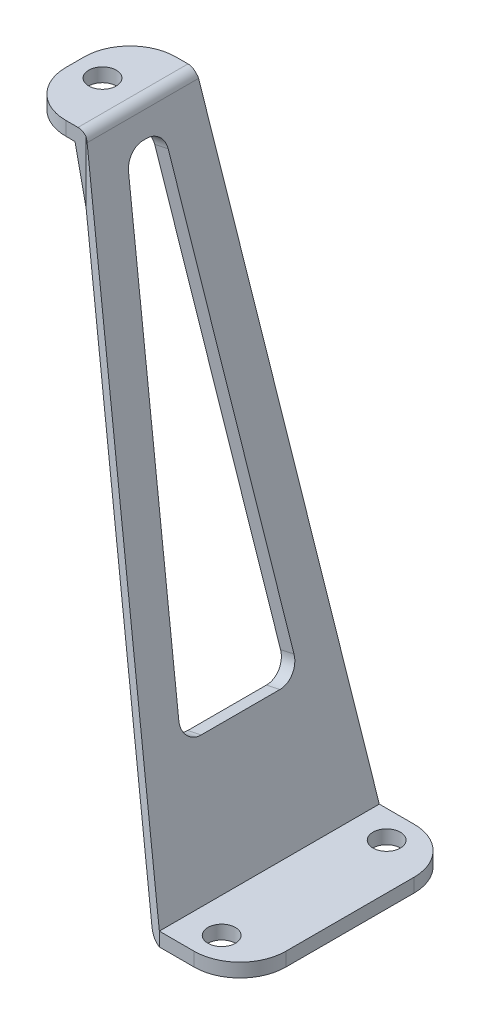
SolidWorks part; units mm, degrees
material "Pure Lead"
ref_plane "Front Plane" through (0, 0, 0) normal (0, 0, 1) x (1, 0, 0)
ref_plane "Top Plane" through (0, 0, 0) normal (0, 1, 0) x (1, 0, 0)
ref_plane "Right Plane" through (0, 0, 0) normal (1, 0, 0) x (0, 0, -1)
sketch "Sketch2" plane through (0, 0, 0) normal (0, 0, 1) x (1, 0, 0)
  line L1 (-13.9865, 65.5) -> (0, 0)
  line L2 (0, 0) -> (8.8, 0)
  line L3 (8.8, 0) -> (8.8, -1.5)
  line L4 (8.8, -1.5) -> (-1.2135, -1.5)
  line L8 (-21.2, 65.5) -> (-13.9865, 65.5)
  line L9 (-1.2135, -1.5) -> (-15.2, 64)
  line L10 (-15.2, 64) -> (-21.2, 64)
  line L12 (-21.2, 65.5) -> (-21.2, 64)
  dimension "D1" = 6
  dimension "D2" = 8.8
  dimension "D3" = 1.5
  dimension "D4" = 1.5
  dimension "D5" = 30
  dimension "D6" = 65.5
  dimension "D7" = 1.5
extrude "Boss-Extrude1" add sketch "Sketch2" along normal mid plane 24
sketch "Sketch3" plane through (0, 0, 0) normal (0, 1, 0) x (1, 0, 0)
  line L0 (8.8, 12) -> (0, 12) construction
  line L2 (8.8, -12) -> (8.8, 12) construction
  circle A0 centre (3.8, 9) radius 1.5
  circle A1 centre (3.8, -9) radius 1.5
  dimension "D3" = 3
  dimension "D4" = 3
  dimension "D1" = 18
  dimension "D2" = 3
  dimension "D5" = 5
  dimension "D6" = 5
extrude "Cut-Extrude1" cut sketch "Sketch3" against normal through all
sketch "Sketch4" plane through (0, 65.5, 0) normal (0, 1, 0) x (1, 0, 0)
  line L0 (-13.9865, 0) -> (-19.8958, 0) construction
  line L1 (-13.9865, -12) -> (-13.9865, 12) construction
  line L2 (-21.2, -12) -> (-21.2, 12) construction
  circle A0 centre (-18.2, 0) radius 1.5
  dimension "D2" = 3
  dimension "D1" = 3
extrude "Cut-Extrude3" cut sketch "Sketch4" against normal through all
ref_plane "Plane1" through (0, 90, 0) normal (0, 1, 0) x (1, 0, 0)
sketch "Sketch6" plane through (0, 90, 0) normal (0, 1, 0) x (1, 0, 0)
  line L0 (-21.2, 6) -> (-13.9865, 6)
  line L2 (-21.2, -12) -> (-21.2, 12) construction
  line L3 (-13.9865, -12) -> (-13.9865, 12) construction
  line L4 (-21.2, 6) -> (-21.2, -6)
  line L5 (-21.2, -6) -> (-13.9865, -6)
  line L6 (-13.9865, 6) -> (0, 12)
  line L7 (-13.9865, -6) -> (0, -12)
  line L8 (0, 12) -> (8.8, 12)
  line L9 (8.8, 12) -> (8.8, -12)
  line L10 (8.8, -12) -> (0, -12)
extrude "Cut-Extrude4" cut sketch "Sketch6" against normal through all flip side to cut
fillet "Fillet1" radius 5 1 edges at (8.8, -0.75, 12)
fillet "Fillet2" radius 5 1 edges at (8.8, -0.75, -12)
fillet "Fillet3" radius 5 2 edges at (-21.2, 64.75, 6) (-21.2, 64.75, -6)
fillet "Fillet4" radius 1.1 1 edges at (-1.2135, -1.5, 0)
fillet "Fillet5" radius 1.1 1 edges at (-13.9865, 65.5, 0)
sketch "Sketch7" plane through (0, 0, 0) normal (0.978, 0.2088, 0) x (0, 0, -1)
  line L2 (-6.7571, 13.6954) -> (6.2012, 13.6954)
  line L3 (-6.7571, 13.6954) -> (-2.2779, 63.6954)
  line L4 (1.7221, 63.6954) -> (6.2012, 13.6954)
  line L5 (-2.2779, 63.6954) -> (1.7221, 63.6954)
  line L8 (-12, 0) -> (-6.0797, 66.0867) construction
  line L11 (-7, -3.3046) -> (7, -3.3046) construction
  line L12 (6.0797, 66.0867) -> (12, 0) construction
  line L13 (-12, 0) -> (12, 0) construction
  dimension "D1" = 4
  dimension "D2" = 17
  dimension "D3" = 4
  dimension "D4" = 50
extrude "Cut-Extrude5" cut sketch "Sketch7" against normal through all
fillet "Fillet6" radius 2 1 edges at (-14.0347, 62.1345, -1.7221)
fillet "Fillet7" radius 2 1 edges at (-14.0347, 62.1345, 2.2779)
fillet "Fillet8" radius 2 1 edges at (-3.5934, 13.2368, -6.2012)
fillet "Fillet9" radius 2 1 edges at (-3.5934, 13.2368, 6.7571)
